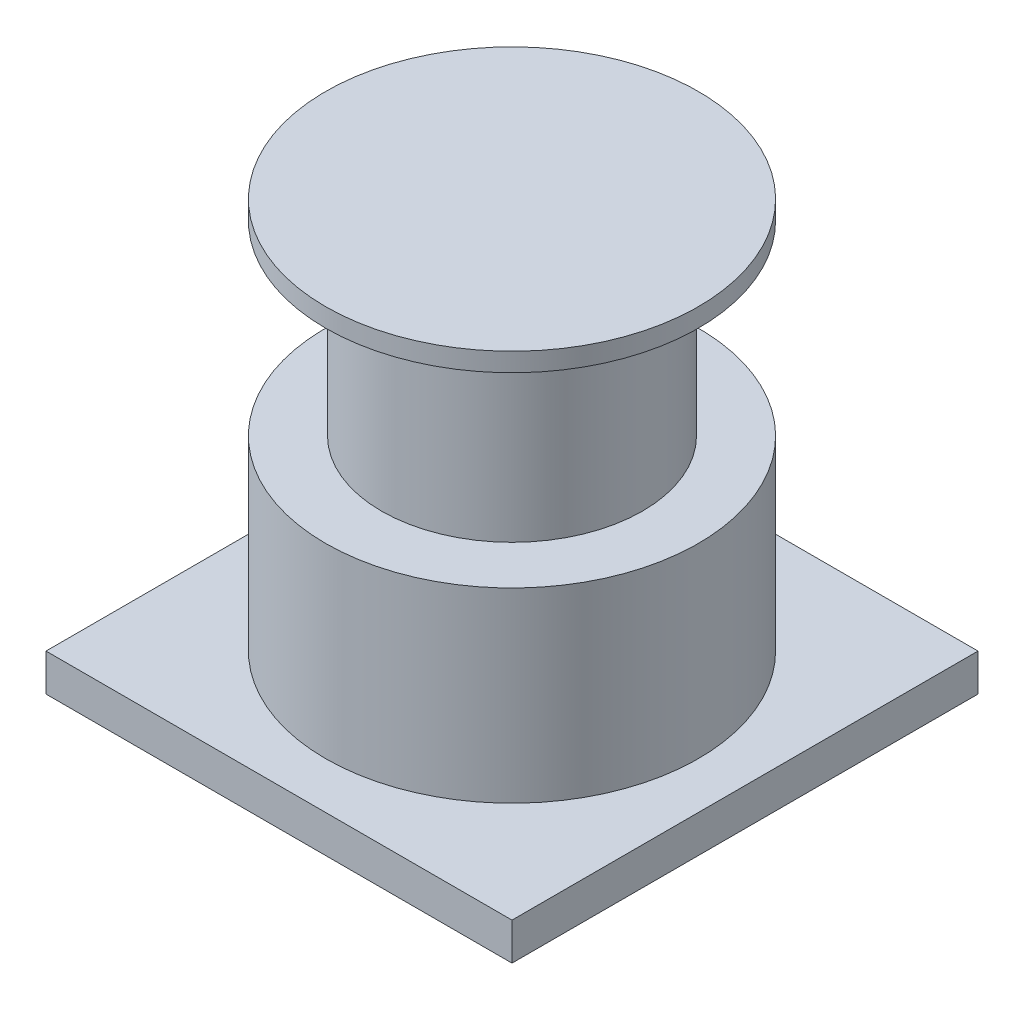
SolidWorks part; units mm, degrees
ref_plane "Front Plane" through (0, 0, 0) normal (0, 0, 1) x (1, 0, 0)
ref_plane "Top Plane" through (0, 0, 0) normal (0, 1, 0) x (1, 0, 0)
ref_plane "Right Plane" through (0, 0, 0) normal (1, 0, 0) x (0, 0, -1)
sketch "Sketch1" plane through (0, 0, 0) normal (0, 1, 0) x (1, 0, 0)
  line L1 (-78.1893, -163.1687) -> (171.8107, -163.1687)
  line L2 (-78.1893, -163.1687) -> (-78.1893, 86.8313)
  line L3 (-78.1893, 86.8313) -> (171.8107, 86.8313)
  line L4 (171.8107, -163.1687) -> (171.8107, 86.8313)
  dimension "D1" = 250
  dimension "D2" = 250
extrude "Boss-Extrude1" add sketch "Sketch1" along normal blind 20
sketch "Sketch2" plane through (0, 20, 0) normal (0, 1, 0) x (1, 0, 0)
  line L0 (171.8107, 86.8313) -> (-78.1893, 86.8313) construction
  line L1 (171.8107, -163.1687) -> (171.8107, 86.8313) construction
  circle A0 centre (46.8107, -38.1687) radius 100
  point P4 (46.8107, 86.8313)
  point P7 (171.8107, -38.1687)
  dimension "D1" = 200
extrude "Boss-Extrude2" add sketch "Sketch2" along normal blind 100
sketch "Sketch3" plane through (0, 120, 0) normal (0, 1, 0) x (1, 0, 0)
  circle A0 centre (46.8107, -38.1687) radius 70
  dimension "D1" = 140
extrude "Boss-Extrude3" add sketch "Sketch3" along normal blind 100
sketch "Sketch4" plane through (0, 220, 0) normal (0, 1, 0) x (1, 0, 0)
  circle A0 centre (46.8107, -38.1687) radius 100
extrude "Boss-Extrude4" add sketch "Sketch4" along normal blind 10
sketch "Sketch5" plane through (0, 0, 0) normal (0, -1, 0) x (1, 0, 0)
  line L0 (-78.1893, 163.1687) -> (171.8107, -86.8313) construction
  line L1 (-78.1893, -86.8313) -> (171.8107, 163.1687) construction
  point P8 (46.8107, 38.1687)
